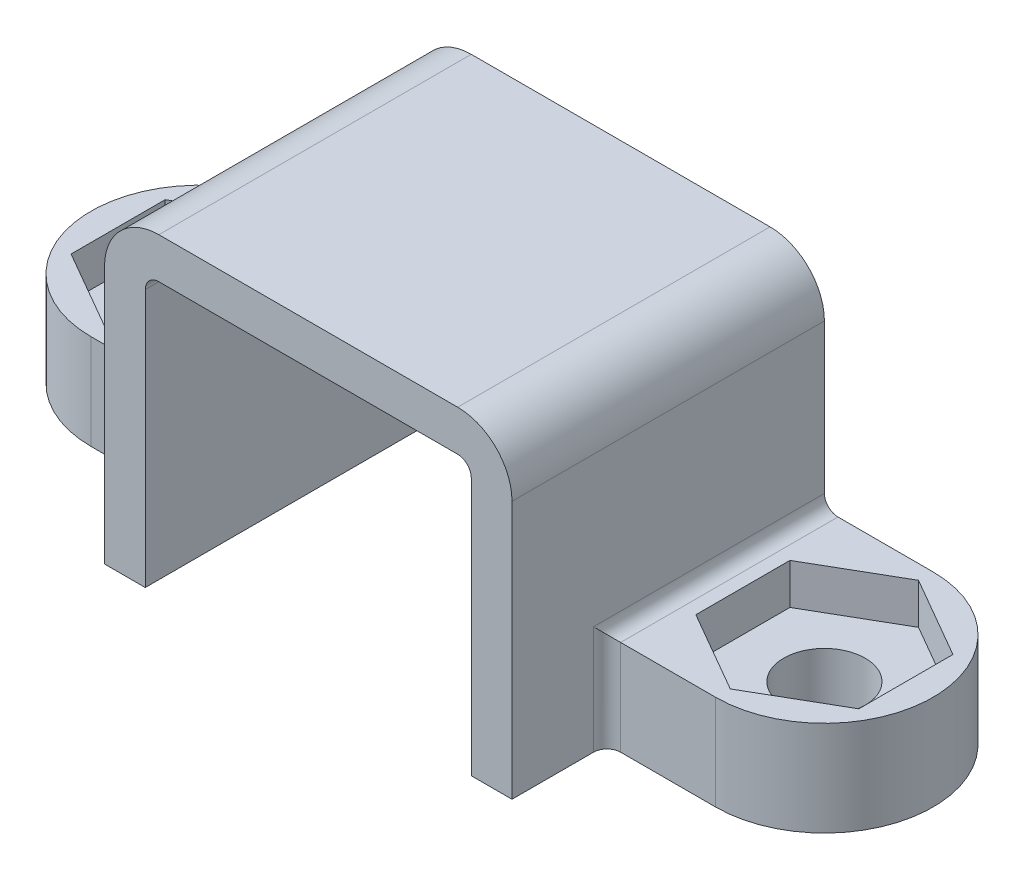
SolidWorks part; units mm, degrees
ref_plane "Front Plane" through (0, 0, 0) normal (0, 0, 1) x (1, 0, 0)
ref_plane "Top Plane" through (0, 0, 0) normal (0, 1, 0) x (1, 0, 0)
ref_plane "Right Plane" through (0, 0, 0) normal (1, 0, 0) x (0, 0, -1)
sketch "Sketch1" plane through (0, 0, 0) normal (0, 1, 0) x (1, 0, 0)
  line L1 (7.5, -5.75) -> (-7.5, -5.75)
  line L2 (7.5, -5.75) -> (7.5, 5.75)
  line L3 (7.5, 5.75) -> (-7.5, 5.75)
  line L4 (-7.5, -5.75) -> (-7.5, 5.75)
  line L5 (7.5, -5.75) -> (-7.5, 5.75) construction
  line L6 (7.5, 5.75) -> (-7.5, -5.75) construction
  point P0 (0, 0)
  dimension "D1" = 15
  dimension "D2" = 11.5
extrude "Boss-Extrude1" add sketch "Sketch1" along normal blind 1.5
sketch "Sketch4" plane through (0, 0, 0) normal (0, -1, 0) x (1, 0, 0)
  line L0 (-7.5, 5.75) -> (7.5, 5.75) construction
  line L1 (-7.5, -5.75) -> (-6, -5.75)
  line L2 (-7.5, -5.75) -> (-7.5, 5.75)
  line L3 (-7.5, 5.75) -> (-6, 5.75)
  line L4 (-6, -5.75) -> (-6, 5.75)
  line L6 (7.5, -5.75) -> (6, -5.75)
  line L7 (7.5, -5.75) -> (7.5, 5.75)
  line L8 (7.5, 5.75) -> (6, 5.75)
  line L9 (6, -5.75) -> (6, 5.75)
  dimension "D1" = 1.5
  dimension "D2" = 1.5
extrude "Boss-Extrude2" add sketch "Sketch4" along normal blind 10
ref_plane "Plane1" through (0, 0, 0) normal (1, 0, 0) x (0, 0, -1)
sketch "Sketch5" plane through (0, -10, 0) normal (0, -1, 0) x (1, 0, 0)
  line L0 (-6, -5.75) -> (-11.5, -5.75)
  line L1 (-6, 2.25) -> (-11.5, 2.25)
  line L2 (-6, -5.75) -> (-6, 5.75) construction
  line L3 (0, -5.5) -> (0, 5.5) construction
  line L4 (6, -5.75) -> (11.5, -5.75)
  line L5 (6, 2.25) -> (11.5, 2.25)
  line L6 (-6, 2.25) -> (-6, -5.75)
  line L7 (6, 2.25) -> (6, -5.75)
  arc A0 (-11.5, 2.25) -> (-11.5, -5.75) centre (-11.5, -1.75) ccw
  arc A1 (11.5, 2.25) -> (11.5, -5.75) centre (11.5, -1.75) cw
  dimension "D1" = 8
  dimension "D2" = 5.5
extrude "Boss-Extrude3" add sketch "Sketch5" against normal blind 3.5
sketch "Sketch11" plane through (-6, 0, 0) normal (1, 0, 0) x (0, 0, -1)
  line L0 (5.75, -10) -> (-5.75, -10) construction
  line L1 (2.75, -10) -> (0.75, -10)
  line L2 (2.75, -10) -> (2.75, -6.5)
  line L3 (2.75, -6.5) -> (0.75, -6.5)
  line L4 (0.75, -10) -> (0.75, -6.5)
  line L5 (5.75, -10) -> (5.75, 0) construction
  dimension "D1" = 3
  dimension "D2" = 2
  dimension "D3" = 3.5
sketch "Sketch10" plane through (0, -6.5, 0) normal (0, 1, 0) x (1, 0, 0)
  line L7 (-8.5, 3.4821) -> (-11.5, 5.2141)
  line L8 (-11.5, 5.2141) -> (-14.5, 3.4821)
  line L9 (-14.5, 3.4821) -> (-14.5, 0.0179)
  line L10 (-14.5, 0.0179) -> (-11.5, -1.7141)
  line L11 (-11.5, -1.7141) -> (-8.5, 0.0179)
  line L12 (-8.5, 0.0179) -> (-8.5, 3.4821)
  circle A0 centre (-11.5, 1.75) radius 3 construction
  arc A1 (-11.5, 5.75) -> (-11.5, -2.25) centre (-11.5, 1.75) ccw construction
  dimension "D1" = 6
extrude "Cut-Extrude1" cut sketch "Sketch10" against normal blind 1.5
sketch "Sketch12" plane through (0, -6.5, 0) normal (0, 1, 0) x (1, 0, 0)
  circle A0 centre (-11.5, 1.75) radius 1.5
  arc A1 (-11.5, 5.75) -> (-11.5, -2.25) centre (-11.5, 1.75) ccw construction
  dimension "D1" = 3
extrude "Cut-Extrude3" cut sketch "Sketch12" against normal through all
mirror "Mirror1" about plane through (0, 0, 0) normal (1, 0, 0) of "Cut-Extrude3", "Cut-Extrude1"
fillet "Fillet1" radius 2 2 edges at (7.5, 1.5, 0) (-7.5, 1.5, 0)
fillet "Fillet2" radius 0.5 6 edges at (7.5, -6.5, -1.75) (-7.5, -6.5, -1.75) (6, 0, 0) (-6, 0, 0) (7.5, -8.25, 2.25) (-7.5, -8.25, 2.25)
